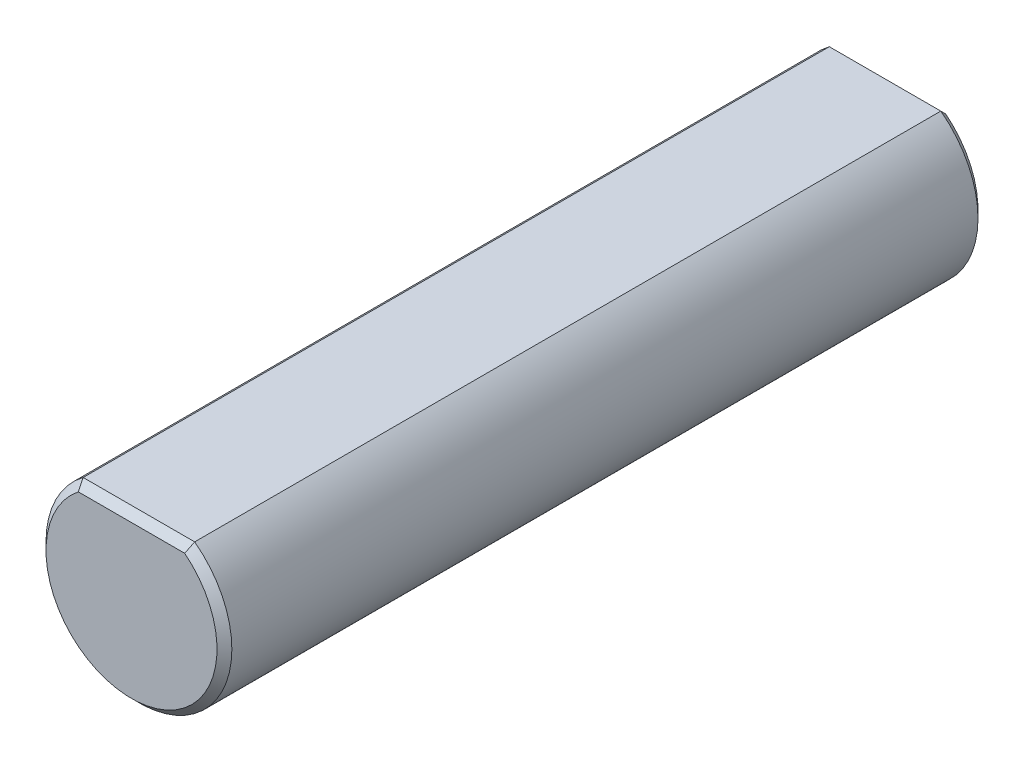
SolidWorks part; units mm, degrees
ref_plane "Front Plane" through (0, 0, 0) normal (0, 0, 1) x (1, 0, 0)
ref_plane "Top Plane" through (0, 0, 0) normal (0, 1, 0) x (1, 0, 0)
ref_plane "Right Plane" through (0, 0, 0) normal (1, 0, 0) x (0, 0, -1)
sketch "Sketch1" plane through (0, 0, 0) normal (0, 0, 1) x (1, 0, 0)
  line L1 (1.905, 2.54) -> (-1.905, 2.54)
  arc A0 (-1.905, 2.54) -> (1.905, 2.54) centre (0, 0) ccw
  dimension "D1" = 6.35
  dimension "D2" = 5.715
extrude "Boss-Extrude1" add sketch "Sketch1" along normal mid plane 26
chamfer "Chamfer1" distance 0.254 angle 45 4 edges at (0, 2.54, 13) (0, -3.175, 13) (0, 2.54, -13) (0, -3.175, -13)
